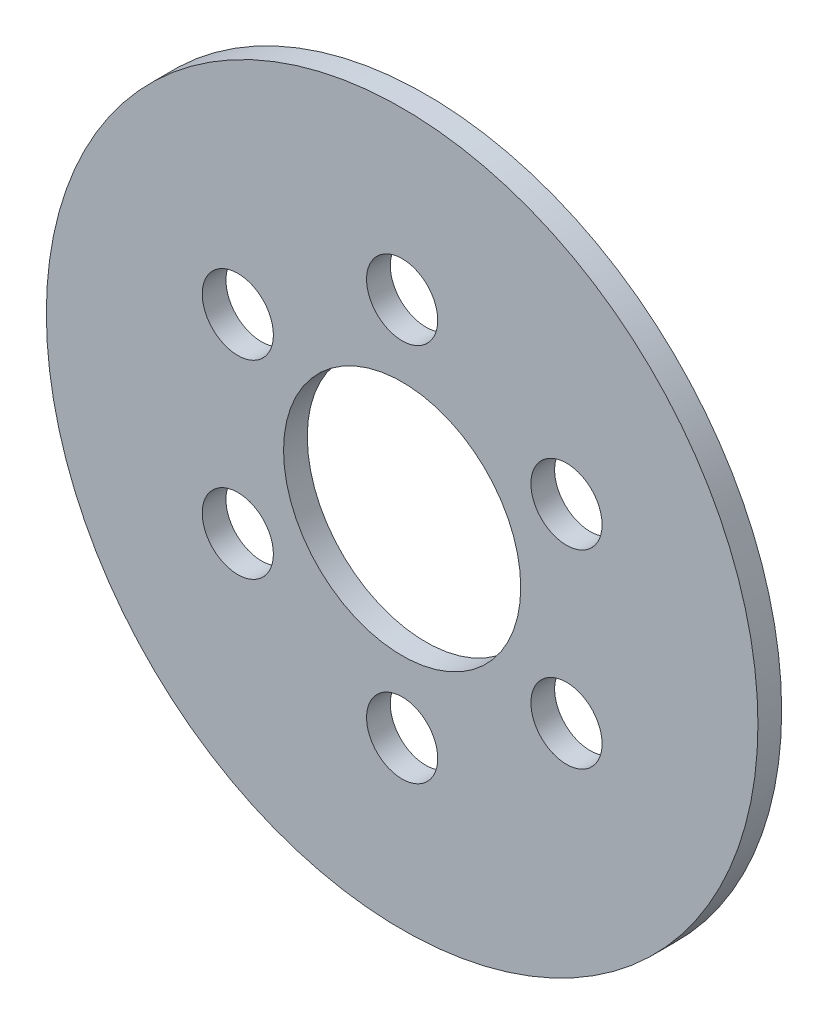
SolidWorks part; units mm, degrees
material "环氧玻璃布层压板"
ref_plane "前视基准面" through (0, 0, 0) normal (0, 0, 1) x (1, 0, 0)
ref_plane "上视基准面" through (0, 0, 0) normal (0, 1, 0) x (1, 0, 0)
ref_plane "右视基准面" through (0, 0, 0) normal (1, 0, 0) x (0, 0, -1)
sketch "草图1" plane through (0, 0, 0) normal (0, 0, 1) x (1, 0, 0)
  circle A0 centre (0, 0) radius 15
  circle A1 centre (0, 0) radius 8 construction
  circle A2 centre (0, 8) radius 1.5
  circle A3 centre (6.9282, 4) radius 1.5
  circle A4 centre (6.9282, -4) radius 1.5
  circle A5 centre (0, -8) radius 1.5
  circle A6 centre (-6.9282, -4) radius 1.5
  circle A7 centre (-6.9282, 4) radius 1.5
  circle A8 centre (0, 0) radius 5
  point P18 (0, 0)
  dimension "D1" = 30
  dimension "D2" = 16
  dimension "D3" = 3
  dimension "D5" = 10
  dimension "D4" = 6
extrude "凸台-拉伸1" add sketch "草图1" along normal blind 1
